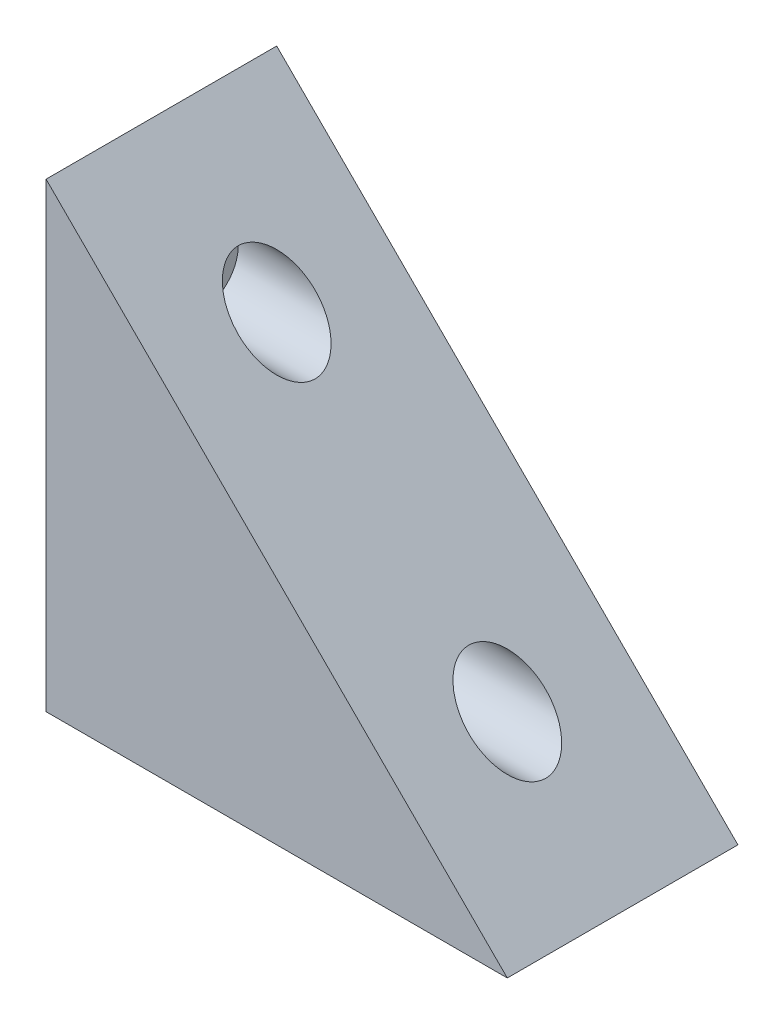
SolidWorks part; units mm, degrees
ref_plane "정면" through (0, 0, 0) normal (0, 0, 1) x (1, 0, 0)
ref_plane "윗면" through (0, 0, 0) normal (0, 1, 0) x (1, 0, 0)
ref_plane "우측면" through (0, 0, 0) normal (1, 0, 0) x (0, 0, -1)
sketch "스케치1" plane through (0, 0, 0) normal (0, 0, 1) x (1, 0, 0)
  line L0 (0, 0) -> (0, 60)
  line L1 (0, 60) -> (60, 0)
  line L2 (60, 0) -> (0, 0)
  dimension "D1" = 60
  dimension "D2" = 60
extrude "보스-돌출1" add sketch "스케치1" along normal blind 30
sketch "스케치2" plane through (0, 0, 0) normal (-1, 0, 0) x (0, 0, 1)
  line L0 (0, 60) -> (0, 0) construction
  line L1 (30, 0) -> (0, 0) construction
  line L2 (30, 60) -> (0, 60) construction
  line L3 (30, 60) -> (30, 0) construction
  circle A0 centre (15, 15) radius 3
  circle A1 centre (15, 45) radius 3
  dimension "D3" = 6
  dimension "D4" = 6
  dimension "D1" = 15
  dimension "D2" = 15
  dimension "D5" = 15
  dimension "D6" = 15
extrude "컷-돌출1" cut sketch "스케치2" against normal blind 60
ref_plane "평면1" through (5, 0, 0) normal (-1, 0, 0) x (0, 0, 1)
sketch "스케치3" plane through (5, 0, 0) normal (-1, 0, 0) x (0, 0, 1)
  circle A0 centre (15, 15) radius 5
  circle A1 centre (15, 15) radius 3 construction
  circle A2 centre (15, 45) radius 5
  dimension "D1" = 10
  dimension "D2" = 10
extrude "컷-돌출2" cut sketch "스케치3" against normal blind 60
